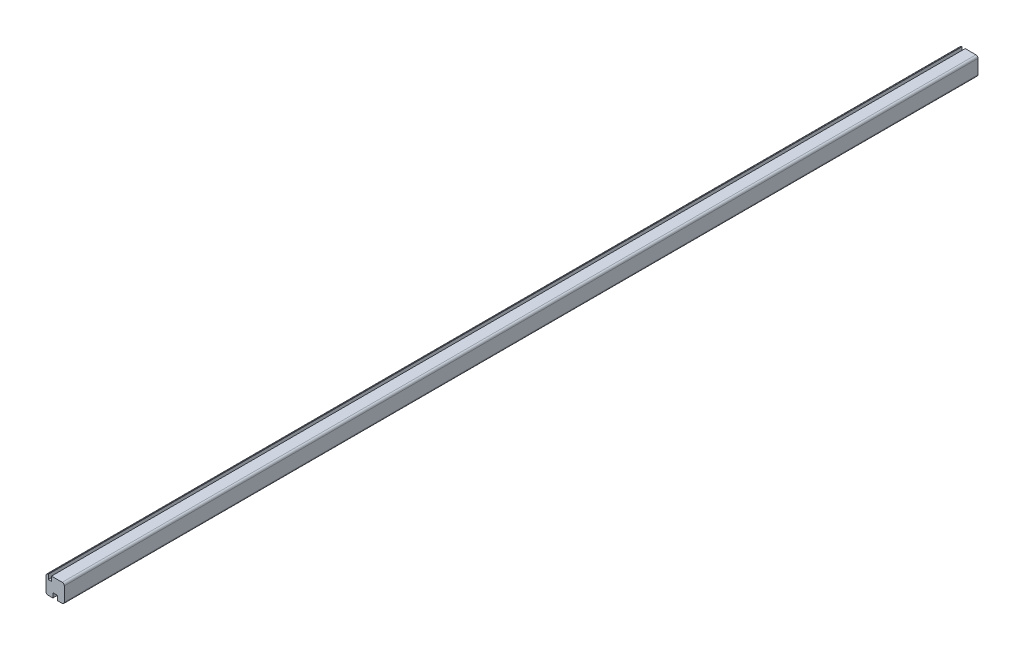
SolidWorks part; units mm, degrees
ref_plane "Front Plane" through (0, 0, 0) normal (0, 0, 1) x (1, 0, 0)
ref_plane "Top Plane" through (0, 0, 0) normal (0, 1, 0) x (1, 0, 0)
ref_plane "Right Plane" through (0, 0, 0) normal (1, 0, 0) x (0, 0, -1)
sketch "Sketch1" plane through (0, 0, 0) normal (0, 0, 1) x (1, 0, 0)
  line L0 (0, 0) -> (0, -50000) construction
  line L1 (-15.5, -20) -> (-5, -20)
  line L2 (-20, -15.5) -> (-20, 15.5)
  line L3 (-15.5, 20) -> (-15, 20)
  line L4 (20, -15.5) -> (20, 15.5)
  line L5 (-20, -20) -> (20, 20) construction
  line L6 (-20, 20) -> (20, -20) construction
  line L8 (-5, -20) -> (-5, -10)
  line L9 (-5, -10) -> (5, -10)
  line L10 (5, -20) -> (5, -10)
  line L12 (-15, 20) -> (-15, 10)
  line L13 (-15, 10) -> (-8, 10)
  line L14 (-8, 20) -> (-8, 10)
  line L15 (5, -20) -> (15.5, -20)
  line L16 (-8, 20) -> (15.5, 20)
  arc A0 (-20, 15.5) -> (-15.5, 20) centre (-15.5, 15.5) cw
  arc A1 (-15.5, -20) -> (-20, -15.5) centre (-15.5, -15.5) cw
  arc A2 (15.5, -20) -> (20, -15.5) centre (15.5, -15.5) ccw
  arc A3 (15.5, 20) -> (20, 15.5) centre (15.5, 15.5) cw
  point P0 (0, 0)
  dimension "D8" = 4.5
  dimension "D1" = 40
  dimension "D2" = 40
  dimension "D3" = 15
  dimension "D4" = 10
  dimension "D5" = 5
  dimension "D6" = 28
  dimension "D7" = 10
extrude "Boss-Extrude1" add sketch "Sketch1" along normal blind 2000
